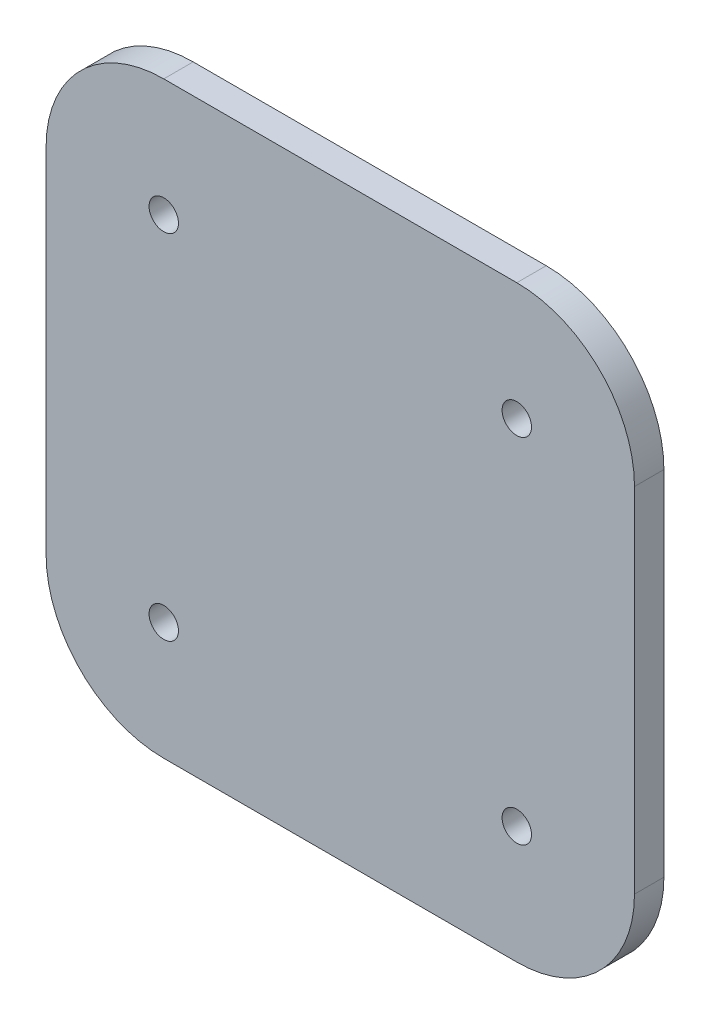
SolidWorks part; units mm, degrees
ref_plane "Plan de face" through (0, 0, 0) normal (0, 0, 1) x (1, 0, 0)
ref_plane "Plan de dessus" through (0, 0, 0) normal (0, 1, 0) x (1, 0, 0)
ref_plane "Plan de droite" through (0, 0, 0) normal (1, 0, 0) x (0, 0, -1)
sketch "Esquisse1" plane through (0, 0, 0) normal (0, 0, 1) x (1, 0, 0)
  line L1 (-70.3611, 39.6365) -> (29.6389, 39.6365)
  line L2 (-70.3611, 39.6365) -> (-70.3611, -60.3635)
  line L3 (-70.3611, -60.3635) -> (29.6389, -60.3635)
  line L4 (29.6389, 39.6365) -> (29.6389, -60.3635)
  dimension "D1" = 100
  dimension "D2" = 100
extrude "Boss.-Extru.1" add sketch "Esquisse1" along normal blind 5
sketch "Esquisse2" plane through (0, 0, 5) normal (0, 0, 1) x (1, 0, 0)
  line L0 (29.6389, 39.6365) -> (-70.3611, 39.6365) construction
  line L1 (-70.3611, 39.6365) -> (-70.3611, -60.3635) construction
  line L2 (-70.3611, -60.3635) -> (29.6389, -60.3635) construction
  line L3 (29.6389, -60.3635) -> (29.6389, 39.6365) construction
  circle A0 centre (-50.3611, 19.6365) radius 2.5
  circle A1 centre (-50.3611, -40.3635) radius 2.5
  circle A2 centre (9.6389, -40.3635) radius 2.5
  circle A3 centre (9.6389, 19.6365) radius 2.5
  dimension "D1" = 5
  dimension "D5" = 5
  dimension "D6" = 5
  dimension "D8" = 5
  dimension "D9" = 20
  dimension "D2" = 20
  dimension "D3" = 20
  dimension "D4" = 20
  dimension "D7" = 20
  dimension "D10" = 20
  dimension "D11" = 20
  dimension "D12" = 20
  dimension "D13" = 20
extrude "Enlèv. mat.-Extru.1" cut sketch "Esquisse2" against normal blind 5
fillet "Congé1" radius 20 4 edges at (29.6389, 39.6365, 2.5) (29.6389, -60.3635, 2.5) (-70.3611, -60.3635, 2.5) (-70.3611, 39.6365, 2.5)
